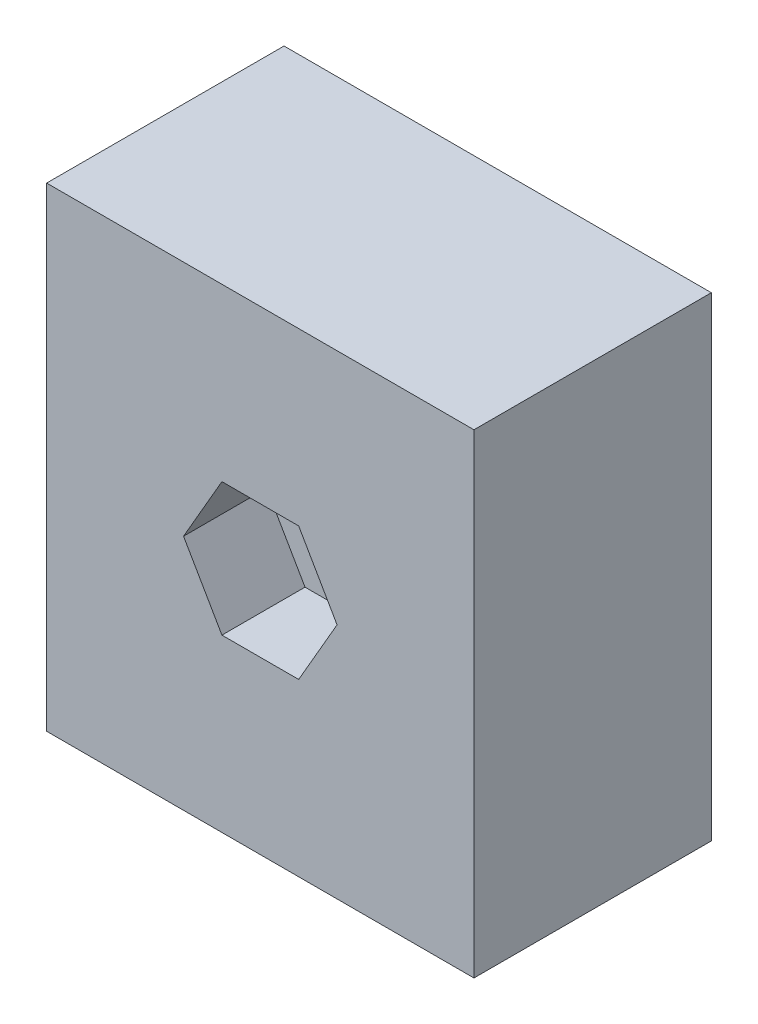
SolidWorks part; units mm, degrees
ref_plane "Front Plane" through (0, 0, 0) normal (0, 0, 1) x (1, 0, 0)
ref_plane "Top Plane" through (0, 0, 0) normal (0, 1, 0) x (1, 0, 0)
ref_plane "Right Plane" through (0, 0, 0) normal (1, 0, 0) x (0, 0, -1)
sketch "Sketch1" plane through (0, 0, 0) normal (0, 0, 1) x (1, 0, 0)
  line L1 (-9, -10) -> (9, -10)
  line L2 (-9, -10) -> (-9, 10)
  line L3 (-9, 10) -> (9, 10)
  line L4 (9, -10) -> (9, 10)
  line L5 (-9, -10) -> (9, 10) construction
  line L6 (-9, 10) -> (9, -10) construction
  point P0 (0, 0)
  dimension "D1" = 18
  dimension "D2" = 20
extrude "Boss-Extrude1" add sketch "Sketch1" along normal blind 10
sketch "Sketch2" plane through (0, 0, 10) normal (0, 0, 1) x (1, 0, 0)
  line L0 (9, 10) -> (-9, -10) construction
  circle A0 centre (0, 0) radius 1.8
  dimension "D1" = 3.6
extrude "Cut-Extrude1" cut sketch "Sketch2" against normal through all contours A0 L0 | L0 A0
sketch "Sketch3" plane through (0, 0, 10) normal (0, 0, 1) x (1, 0, 0)
  line L7 (1.6166, 2.8) -> (-1.6166, 2.8)
  line L8 (-1.6166, 2.8) -> (-3.2332, 0)
  line L9 (-3.2332, 0) -> (-1.6166, -2.8)
  line L10 (-1.6166, -2.8) -> (1.6166, -2.8)
  line L11 (1.6166, -2.8) -> (3.2332, 0)
  line L12 (3.2332, 0) -> (1.6166, 2.8)
  circle A1 centre (0, 0) radius 2.8 construction
  dimension "D1" = 5.6
extrude "Cut-Extrude2" cut sketch "Sketch3" against normal blind 3.5
